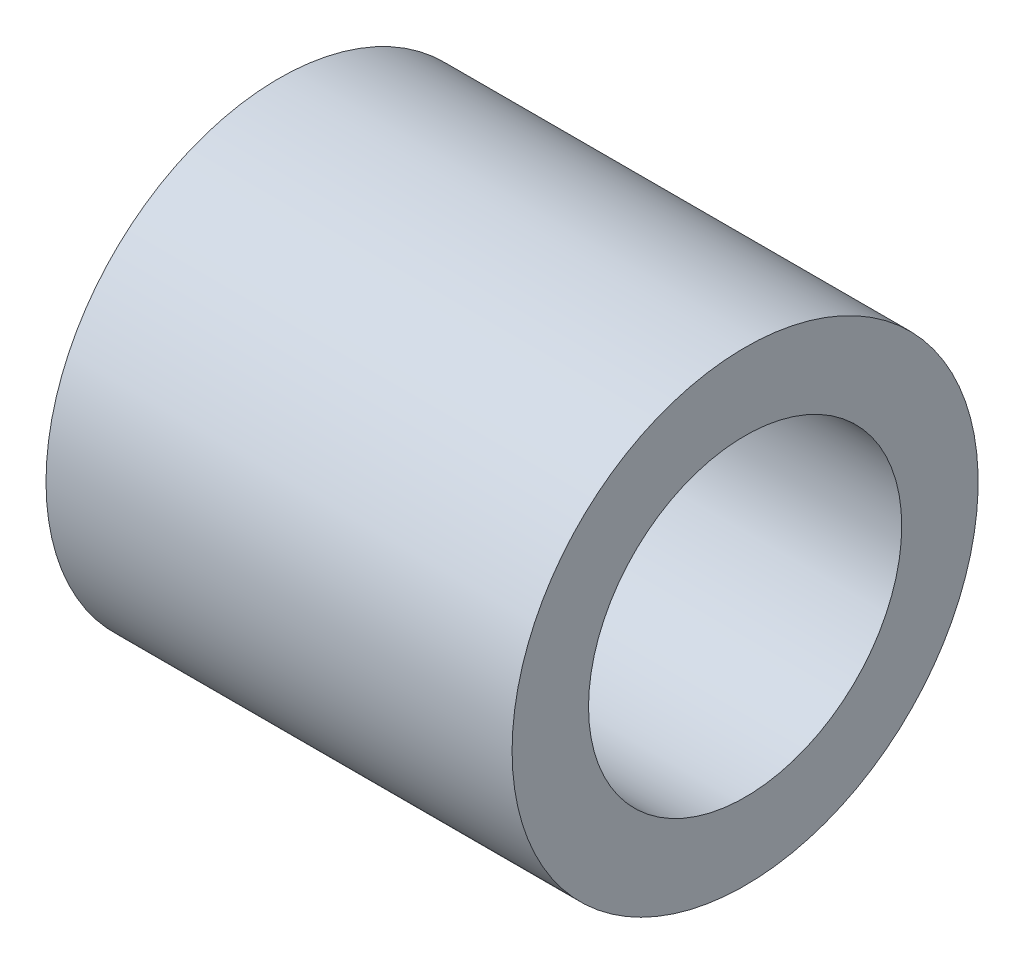
SolidWorks part; units mm, degrees
ref_plane "Front Plane" through (0, 0, 0) normal (0, 0, 1) x (1, 0, 0)
ref_plane "Top Plane" through (0, 0, 0) normal (0, 1, 0) x (1, 0, 0)
ref_plane "Right Plane" through (0, 0, 0) normal (1, 0, 0) x (0, 0, -1)
sketch "Sketch1" plane through (0, 0, 0) normal (1, 0, 0) x (0, 0, -1)
  circle A0 centre (0, 0) radius 4.7625
  dimension "D1" = 9.525
extrude "Boss-Extrude1" add sketch "Sketch1" along normal blind 9.525
sketch "Sketch2" plane through (0, 0, 0) normal (-1, 0, 0) x (0, 0, 1)
  circle A0 centre (0, 0) radius 3.2004
  dimension "D1" = 6.4008
extrude "Cut-Extrude1" cut sketch "Sketch2" against normal blind 9.525
